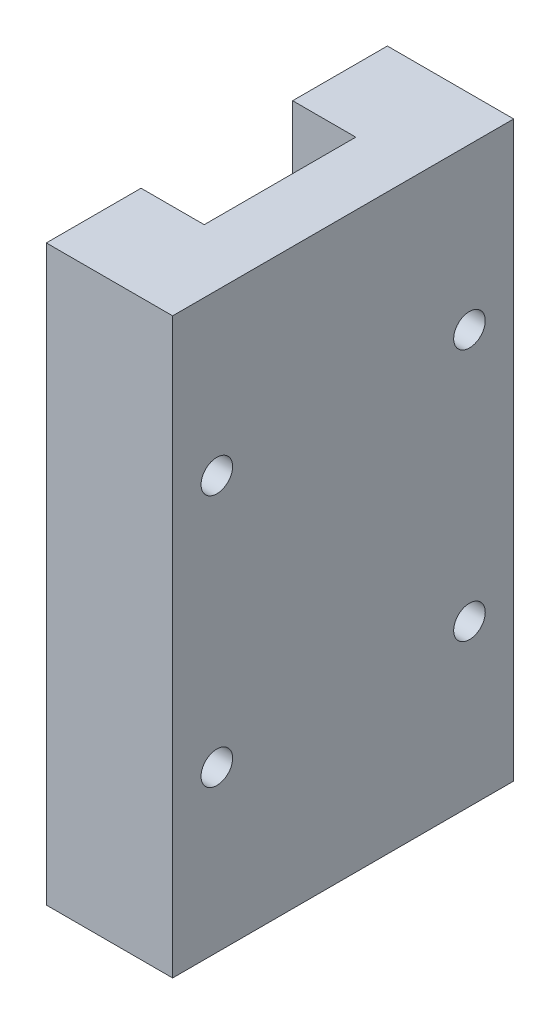
SolidWorks part; units mm, degrees
ref_plane "前基準面" through (0, 0, 0) normal (0, 0, 1) x (1, 0, 0)
ref_plane "上基準面" through (0, 0, 0) normal (0, 1, 0) x (1, 0, 0)
ref_plane "右基準面" through (0, 0, 0) normal (1, 0, 0) x (0, 0, -1)
sketch "草圖1" plane through (0, 0, 0) normal (1, 0, 0) x (0, 0, -1)
  line L0 (0, 0) -> (0, 57.6932) construction
  line L1 (-13.5, -22.7) -> (13.5, -22.7)
  line L2 (-13.5, -22.7) -> (-13.5, 22.7)
  line L3 (-13.5, 22.7) -> (13.5, 22.7)
  line L4 (13.5, -22.7) -> (13.5, 22.7)
  line L5 (0, 0) -> (33.7917, 0) construction
  dimension "D1" = 27
  dimension "D2" = 45.4
extrude "伸長1" add sketch "草圖1" along normal blind 10
sketch "草圖2" plane through (0, -22.7, 0) normal (0, -1, 0) x (1, 0, 0)
  line L0 (0, 0) -> (10, 0) construction
  line L1 (10, 13.5) -> (10, -13.5) construction
  line L2 (0, 13.5) -> (0, -13.5) construction
  line L3 (0, 6) -> (5, 6)
  line L4 (0, 6) -> (0, -6)
  line L5 (0, -6) -> (5, -6)
  line L6 (5, 6) -> (5, -6)
  dimension "D1" = 12
  dimension "D2" = 5
extrude "除料-伸長1" cut sketch "草圖2" against normal through all
hole_wizard "M3 螺紋孔1" positions "3D草圖1" profile "草圖3" tap size "M3" standard "ISO"
sketch3d "3D草圖1"
  point P0 (10, 10, -10)
  point P2 (10, -10, -10)
  point P4 (10, 10, 10)
  point P6 (10, -10, 10)
  dimension "D1" = 20
  dimension "D2" = 20
  dimension "D3" = 3.5
  dimension "D4" = 12.7
sketch "草圖3" plane through (10, 10, -10) normal (0, 1, 0) x (0, 0, -1)
  line L0 (0, 0) -> (0, 5.2511)
  line L1 (0, 5.2511) -> (1.25, 4.5)
  line L2 (1.25, 4.5) -> (1.25, 0)
  line L5 (1.25, 0) -> (0, 0)
  line L10 (0, 5.2511) -> (-1.25, 4.5) construction
  line L11 (0, -6.35) -> (0, 107.95) construction
  dimension "螺孔鑽直徑" = 2.5
  dimension "螺孔鑽深度" = 4.5
  dimension "導頭角度" = 118
cosmetic thread "鑽孔螺紋1" parameters "D2"=12.5
cosmetic thread "鑽孔螺紋2" parameters "D2"=12.5
cosmetic thread "鑽孔螺紋3" parameters "D2"=12.5
cosmetic thread "鑽孔螺紋4" parameters "D2"=12.5
sketch "草圖4" plane through (0, 22.7, 0) normal (0, 1, 0) x (1, 0, 0)
  line L0 (10, 13.5) -> (10, -13.5) construction
  line L1 (10, 13.5) -> (0, 13.5) construction
  circle A0 centre (6.9637, -2.5) radius 1.6637
  dimension "D1" = 3.3274
  dimension "D2" = 3.0363
  dimension "D3" = 16
extrude "伸長2" [suppressed] add sketch "草圖4" along normal blind 4.5
